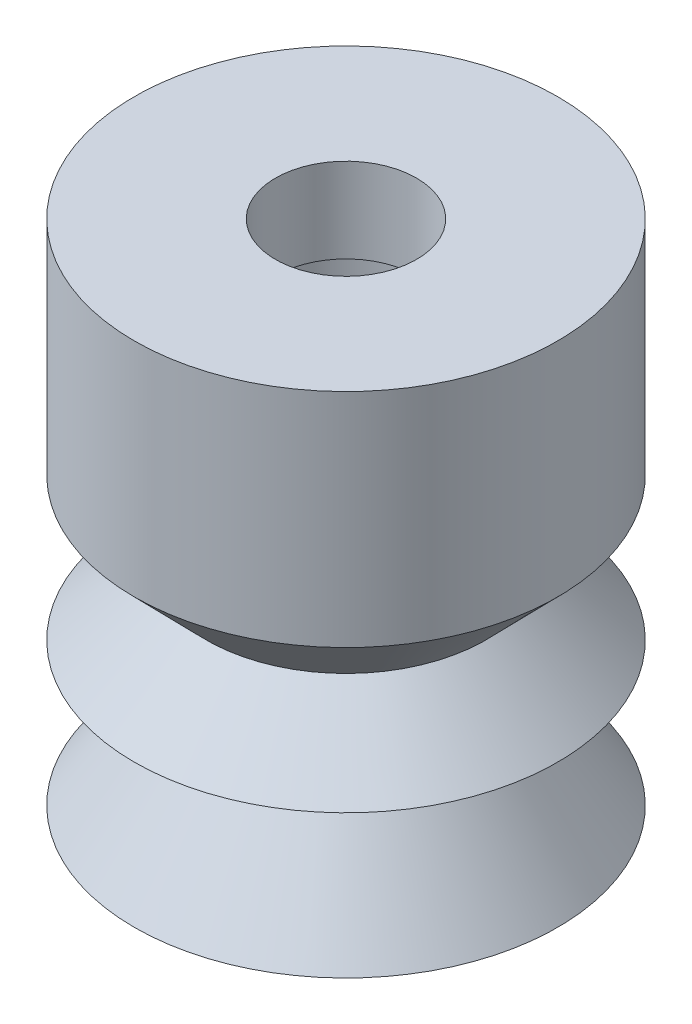
SolidWorks part; units mm, degrees
ref_plane "Plan de face" through (0, 0, 0) normal (0, 0, 1) x (1, 0, 0)
ref_plane "Plan de dessus" through (0, 0, 0) normal (0, 1, 0) x (1, 0, 0)
ref_plane "Plan de droite" through (0, 0, 0) normal (1, 0, 0) x (0, 0, -1)
sketch "Esquisse1" plane through (0, 0, 0) normal (0, 0, 1) x (1, 0, 0)
  line L0 (0, 0) -> (0, 18) construction
  line L2 (-2.5, 18) -> (-7.5, 18)
  line L3 (-7.5, 18) -> (-7.5, 10.1415)
  line L4 (-7.5, 10.1415) -> (-4.9514, 7.5442)
  line L5 (-4.9514, 7.5442) -> (-7.5, 5.0707)
  line L6 (-7.5, 5.0707) -> (-4.9514, 3.607)
  line L7 (-4.9514, 3.607) -> (-7.5, 0)
  line L8 (-7.5, 0) -> (-7.337, 0)
  line L9 (-7.337, 0) -> (-3.5, 3.607)
  line L10 (-3.5, 3.607) -> (-6.0486, 5.0707)
  line L11 (-6.0486, 5.0707) -> (-2, 9)
  line L15 (-7.5, 10.1415) -> (-7.5, 0) construction
  line L16 (-4.9514, 7.5442) -> (-4.9514, 3.607) construction
  line L17 (-2, 9) -> (-2, 13)
  line L18 (-2, 13) -> (-3.4, 13)
  line L19 (-3.4, 13) -> (-3.4, 15)
  line L20 (-3.4, 15) -> (-2.5, 15)
  line L21 (-2.5, 15) -> (-2.5, 18)
  line L22 (-2.5, 18) -> (0, 18) construction
  line L23 (0, 0) -> (-7.337, 0) construction
  line L24 (-6.0486, 5.0707) -> (-7.5, 5.0707) construction
  line L25 (-3.5, 3.607) -> (-4.9514, 3.607) construction
  dimension "D1" = 7.5
  dimension "D2" = 18
  dimension "D3" = 3
  dimension "D4" = 3.4
  dimension "D5" = 2
  dimension "D6" = 3.5
  dimension "D7" = 4
  dimension "D8" = 2
  dimension "D9" = 2.5
revolve "Révolution1" add sketch "Esquisse1" angle 360 about L0
